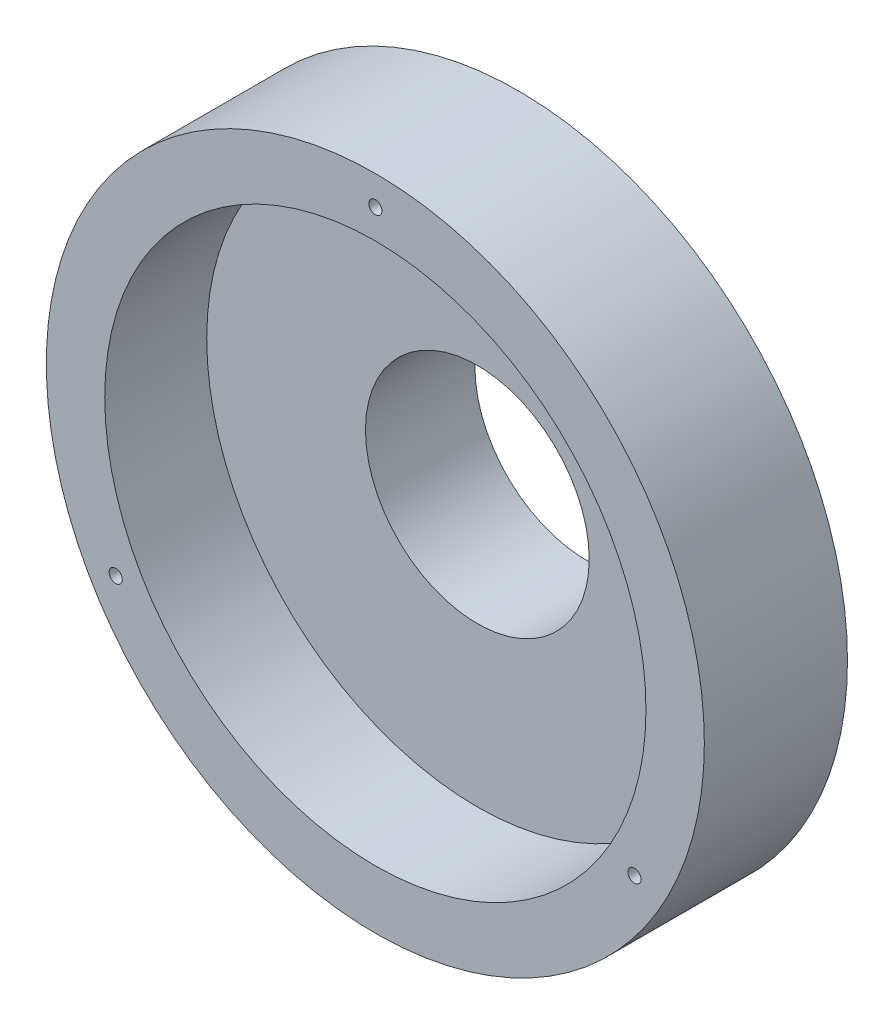
SolidWorks part; units mm, degrees
ref_plane "Front Plane" through (0, 0, 0) normal (0, 0, 1) x (1, 0, 0)
ref_plane "Top Plane" through (0, 0, 0) normal (0, 1, 0) x (1, 0, 0)
ref_plane "Right Plane" through (0, 0, 0) normal (1, 0, 0) x (0, 0, -1)
sketch "Sketch1" plane through (0, 0, 0) normal (0, 0, 1) x (1, 0, 0)
  circle A0 centre (0, 0) radius 24
extrude "Boss-Extrude1" add sketch "Sketch1" along normal blind 3.8
sketch "Sketch2" plane through (0, 0, 3.8) normal (0, 0, 1) x (1, 0, 0)
  circle A0 centre (0, 0) radius 18.7
extrude "Boss-Extrude2" add sketch "Sketch2" along normal blind 4.5
sketch "Sketch3" plane through (0, 0, 3.8) normal (0, 0, 1) x (1, 0, 0)
  line L0 (0, 24) -> (0, 22.2) construction
  circle A0 centre (0, 0) radius 24 construction
  circle A1 centre (0, 22.2) radius 1
  dimension "D1" = 1.8
extrude "Cut-Extrude1" cut sketch "Sketch3" against normal blind 4.5
sketch "Sketch4" plane through (0, 0, 8.3) normal (0, 0, 1) x (1, 0, 0)
  circle A0 centre (0, 0) radius 13.6
extrude "Cut-Extrude2" cut sketch "Sketch4" against normal through all
sketch "Sketch5" plane through (0, 0, 8.3) normal (0, 0, 1) x (1, 0, 0)
  circle A0 centre (0, 0) radius 40
extrude "Boss-Extrude3" add sketch "Sketch5" along normal blind 17.4
sketch "Sketch6" plane through (0, 0, 25.7) normal (0, 0, 1) x (1, 0, 0)
  circle A0 centre (0, 0) radius 32.9
  dimension "D1" = 65.8
extrude "Cut-Extrude6" cut sketch "Sketch6" against normal blind 12.4
sketch "Sketch7" plane through (0, 0, 8.3) normal (0, 0, -1) x (-1, 0, 0)
  circle A0 centre (0, 0) radius 13.6
extrude "Cut-Extrude7" cut sketch "Sketch7" against normal blind 12.4
sketch "Sketch8" plane through (0, 0, 25.7) normal (0, 0, 1) x (1, 0, 0)
  line L0 (0, 40) -> (0, 32.9) construction
  circle A0 centre (0, 0) radius 40 construction
  circle A1 centre (0, 0) radius 32.9 construction
  point P7 (0, 36.45)
  point P11 (31.5017, -18.1875)
  point P12 (-31.5666, -18.15)
  dimension "D1" = 3
hole_wizard "M2x0.4 Tapped Hole1" positions "3DSketch1" profile "Sketch9" tap size "M2x0.4" standard "Ansi Metric"
sketch3d "3DSketch1"
  point P0 (0, 36.45, 25.7)
  point P3 (-31.5666, -18.15, 25.7)
  point P6 (31.5017, -18.1875, 25.7)
sketch "Sketch9" plane through (0, 36.45, 25.7) normal (1, 0, 0) x (0, -1, 0)
  line L0 (0, 0) -> (0, 5.4807)
  line L1 (0, 5.4807) -> (0.8, 5)
  line L2 (0.8, 5) -> (0.8, 0)
  line L5 (0.8, 0) -> (0, 0)
  line L10 (0, 5.4807) -> (-0.8, 5) construction
  line L11 (0, -6.35) -> (0, 107.95) construction
  dimension "Tap Drill Dia." = 1.6
  dimension "Tap Drill Depth" = 5
  dimension "Drill Angle" = 118
